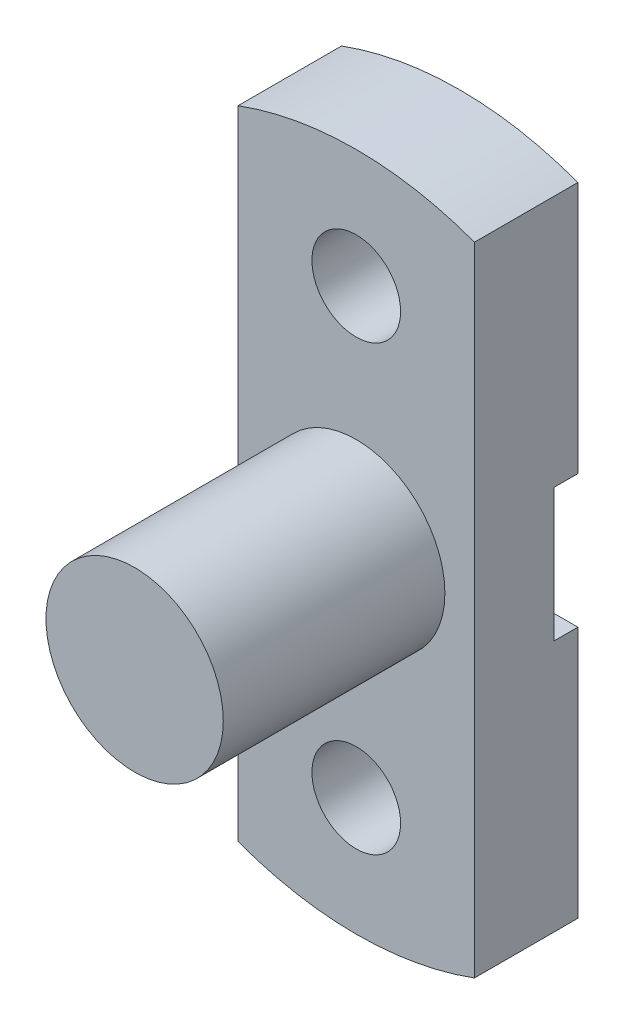
SolidWorks part; units mm, degrees
ref_plane "Front Plane" through (0, 0, 0) normal (0, 0, 1) x (1, 0, 0)
ref_plane "Top Plane" through (0, 0, 0) normal (0, 1, 0) x (1, 0, 0)
ref_plane "Right Plane" through (0, 0, 0) normal (1, 0, 0) x (0, 0, -1)
sketch "Sketch1" plane through (0, 0, 0) normal (0, 0, 1) x (1, 0, 0)
  line L0 (0, 172.5631) -> (0, -153.5571) construction
  line L1 (-40, 107.8193) -> (-40, -107.8193)
  line L2 (40, 107.8193) -> (40, -107.8193)
  arc A0 (-40, -107.8193) -> (40, -107.8193) centre (0, 0) ccw
  arc A1 (40, 107.8193) -> (-40, 107.8193) centre (0, 0) ccw
  circle A3 centre (0, 75) radius 15
  circle A4 centre (0, -75) radius 15
  dimension "D1" = 230
  dimension "D3" = 30
  dimension "D4" = 30
  dimension "D2" = 40
  dimension "D6" = 75
  dimension "D7" = 75
extrude "Boss-Extrude1" add sketch "Sketch1" along normal blind 35
sketch "Sketch3" plane through (40, 0, 0) normal (1, 0, 0) x (0, 0, -1)
  line L0 (0, 107.8193) -> (0, -107.8193) construction
  line L1 (0, 22.5) -> (-8, 22.5)
  line L2 (0, 22.5) -> (0, -22.5)
  line L3 (0, -22.5) -> (-8, -22.5)
  line L4 (-8, 22.5) -> (-8, -22.5)
  dimension "D1" = 45
  dimension "D2" = 22.5
  dimension "D3" = 8
extrude "Cut-Extrude1" cut sketch "Sketch3" against normal blind 115
sketch "Sketch5" plane through (0, 0, 35) normal (0, 0, 1) x (1, 0, 0)
  circle A0 centre (0, 0) radius 30
  dimension "D1" = 60
extrude "Boss-Extrude2" add sketch "Sketch5" along normal blind 75
